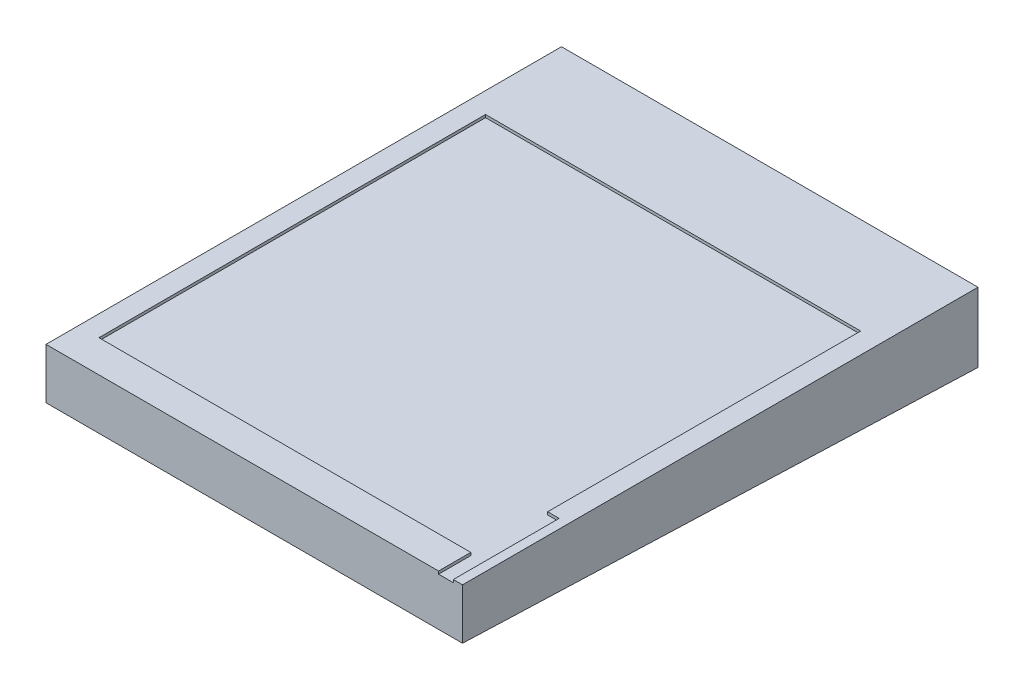
SolidWorks part; units mm, degrees
ref_plane "前视基准面" through (0, 0, 0) normal (0, 0, 1) x (1, 0, 0)
ref_plane "上视基准面" through (0, 0, 0) normal (0, 1, 0) x (1, 0, 0)
ref_plane "右视基准面" through (0, 0, 0) normal (1, 0, 0) x (0, 0, -1)
sketch "草图1" plane through (0, 0, 0) normal (1, 0, 0) x (0, 0, -1)
  line L0 (0, 0) -> (0, -15.1)
  line L1 (0, -15.1) -> (-112, -11)
  line L2 (-112, -11) -> (-112, 0)
  line L3 (-112, 0) -> (0, 0)
  dimension "D1" = 15.1
  dimension "D2" = 112
  dimension "D3" = 11
extrude "凸台-拉伸1" add sketch "草图1" along normal blind 90.5
sketch "草图2" plane through (0, 0, 0) normal (0, 1, 0) x (1, 0, 0)
  line L1 (4.5, -21) -> (86, -21)
  line L2 (4.5, -21) -> (4.5, -105)
  line L3 (4.5, -105) -> (86, -105)
  line L4 (86, -21) -> (86, -105)
  line L5 (4.5, -21) -> (86, -105) construction
  line L6 (4.5, -105) -> (86, -21) construction
  line L7 (90.5, 0) -> (90.5, -112) construction
  line L8 (0, 0) -> (0, -112) construction
  line L9 (90.5, -112) -> (0, -112) construction
  point P4 (45.25, -63)
  dimension "D1" = 7
  dimension "D2" = 4.5
  dimension "D3" = 4.5
  dimension "D4" = 84
extrude "切除-拉伸1" cut sketch "草图2" against normal blind 0.6
sketch "草图3" plane through (0, 0, 0) normal (0, 1, 0) x (1, 0, 0)
  line L0 (90.5, -112) -> (0, -112) construction
  line L1 (88.5, -112) -> (85.3, -112)
  line L2 (88.5, -112) -> (88.5, -89)
  line L3 (88.5, -89) -> (85.3, -89)
  line L4 (85.3, -112) -> (85.3, -89)
  line L5 (88.5, -112) -> (85.3, -89) construction
  line L6 (88.5, -89) -> (85.3, -112) construction
  line L7 (90.5, 0) -> (90.5, -112) construction
  point P4 (86.9, -100.5)
  dimension "D1" = 2
  dimension "D2" = 3.2
  dimension "D3" = 23
extrude "切除-拉伸2" cut sketch "草图3" against normal blind 0.6
